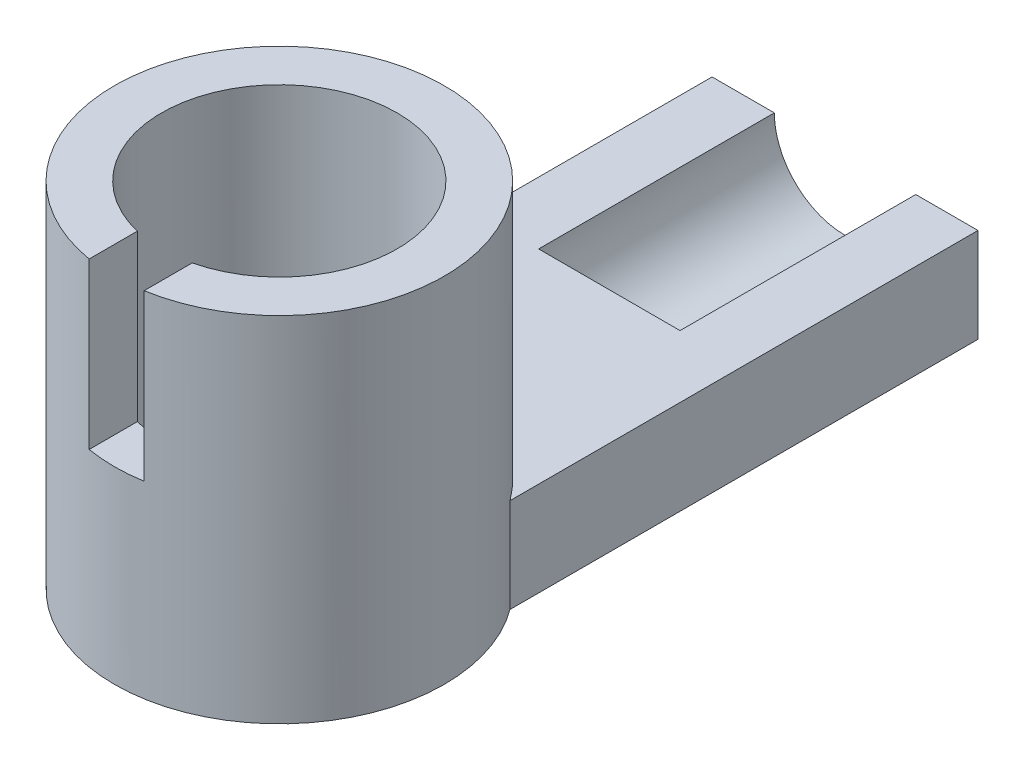
SolidWorks part; units mm, degrees
ref_plane "Front Plane" through (0, 0, 0) normal (0, 0, 1) x (1, 0, 0)
ref_plane "Top Plane" through (0, 0, 0) normal (0, 1, 0) x (1, 0, 0)
ref_plane "Right Plane" through (0, 0, 0) normal (1, 0, 0) x (0, 0, -1)
sketch "Sketch3" plane through (0, 0, 0) normal (0, 1, 0) x (1, 0, 0)
  circle A0 centre (0, 0) radius 50000
  circle A1 centre (0, 0) radius 70000
extrude "Boss-Extrude1" add sketch "Sketch3" along normal blind 150000
sketch "Sketch7" plane through (0, 0, 0) normal (0, -1, 0) x (1, 0, 0)
  line L2 (-56411.2859, -240003.7376) -> (56411.2859, -240003.7376)
  line L3 (-56411.2859, -240003.7376) -> (-56411.2859, -41445.9507)
  line L4 (-56411.2859, -41445.9507) -> (56411.2859, -41445.9507)
  line L5 (56411.2859, -240003.7376) -> (56411.2859, -41445.9507)
  line L6 (-56411.2859, -240003.7376) -> (56411.2859, -41445.9507) construction
  line L7 (-56411.2859, -41445.9507) -> (56411.2859, -240003.7376) construction
  circle A0 centre (0, 0) radius 70000 construction
  point P1 (0, -140724.8442)
extrude "Boss-Extrude3" add sketch "Sketch7" against normal blind 40000
sketch "Sketch8" plane through (0, 0, -240003.7376) normal (0, 0, -1) x (-1, 0, 0)
  line L0 (56411.2859, 40000) -> (-56411.2859, 40000) construction
  circle A0 centre (0, 40000) radius 30000
extrude "Cut-Extrude1" cut sketch "Sketch8" against normal blind 100000
sketch "Sketch9" plane through (0, 40000, 0) normal (0, 1, 0) x (1, 0, 0)
  circle A0 centre (0, 0) radius 50000
extrude "Cut-Extrude2" cut sketch "Sketch9" against normal blind 86482 and the other way blind 26529
sketch "Sketch11" plane through (0, 150000, 0) normal (0, 1, 0) x (1, 0, 0)
  line L1 (-11658.733, 20000) -> (11658.733, 20000)
  line L2 (-11658.733, 20000) -> (-11658.733, -84003.8663)
  line L3 (-11658.733, -84003.8663) -> (11658.733, -84003.8663)
  line L4 (11658.733, 20000) -> (11658.733, -84003.8663)
  line L5 (-11658.733, 20000) -> (11658.733, -84003.8663) construction
  line L6 (-11658.733, -84003.8663) -> (11658.733, 20000) construction
  point P0 (0, -32001.9332)
extrude "Cut-Extrude4" cut sketch "Sketch11" against normal blind 70000 and the other way blind 43724
